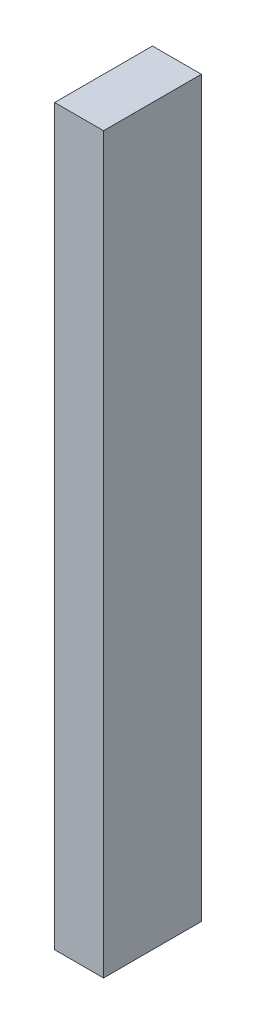
SolidWorks part; units mm, degrees
material "Teak"
ref_plane "Front Plane" through (0, 0, 0) normal (0, 0, 1) x (1, 0, 0)
ref_plane "Top Plane" through (0, 0, 0) normal (0, 1, 0) x (1, 0, 0)
ref_plane "Right Plane" through (0, 0, 0) normal (1, 0, 0) x (0, 0, -1)
sketch "Sketch1" plane through (0, 0, 0) normal (0, 1, 0) x (1, 0, 0)
  line L1 (0, 0) -> (50.8, 0)
  line L2 (0, 0) -> (0, 101.6)
  line L3 (0, 101.6) -> (50.8, 101.6)
  line L4 (50.8, 0) -> (50.8, 101.6)
  dimension "D1" = 101.6
  dimension "D2" = 50.8
extrude "Boss-Extrude1" add sketch "Sketch1" along normal blind 762
